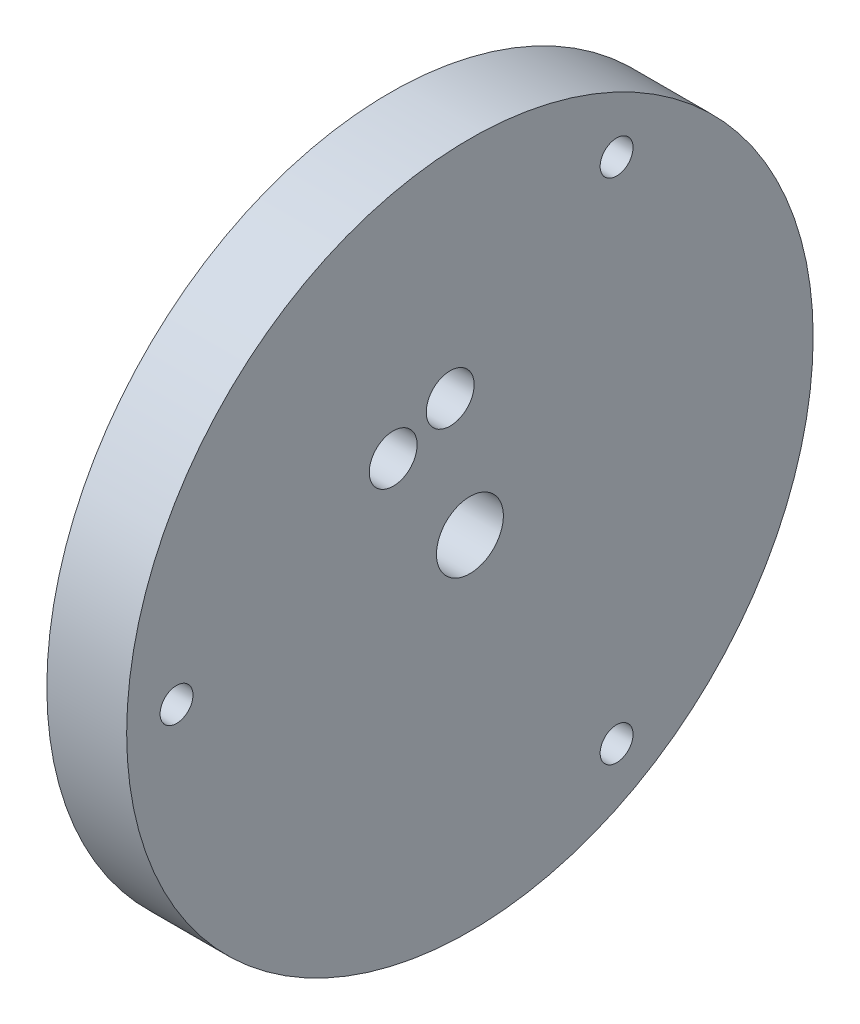
SolidWorks part; units mm, degrees
material "AISI 1010 Steel, hot rolled bar"
ref_plane "Front Plane" through (0, 0, 0) normal (0, 0, 1) x (1, 0, 0)
ref_plane "Top Plane" through (0, 0, 0) normal (0, 1, 0) x (1, 0, 0)
ref_plane "Right Plane" through (0, 0, 0) normal (1, 0, 0) x (0, 0, -1)
sketch "Axial profile (mm)" plane through (0, 0, 0) normal (0, 0, 1) x (1, 0, 0)
  line L0 (-110, 0) -> (75, 0) construction
  line L1 (148.7, 3.35) -> (156.7, 3.35)
  line L2 (156.7, 3.35) -> (156.7, 34.4)
  line L3 (156.7, 34.4) -> (148.7, 34.4)
  line L4 (148.7, 34.4) -> (148.7, 3.35)
revolve "Full revolution" add sketch "Axial profile (mm)" angle 360 about L0
sketch "Sketch2" plane through (0, 0, 0) normal (1, 0, 0) x (0, 0, -1)
  circle A0 centre (-1.9774, 12.8487) radius 2.4
  circle A1 centre (-7.6872, 10.4836) radius 2.4
  circle A2 centre (-29.4, 0) radius 1.65
  circle A3 centre (14.7, -25.4611) radius 1.65
  circle A4 centre (14.7, 25.4611) radius 1.65
extrude "Axial holes" cut sketch "Sketch2" along normal through all and the other way through all
sketch "Sketch3" plane through (0, 0, 0) normal (1, 0, 0) x (0, 0, -1)
  circle A0 centre (-12, 0) radius 1.65
  circle A1 centre (6, -10.3923) radius 1.65
  circle A2 centre (6, 10.3923) radius 1.65
extrude "Cut-Extrude2" cut sketch "Sketch3" along normal blind 6 from offset 148.7
